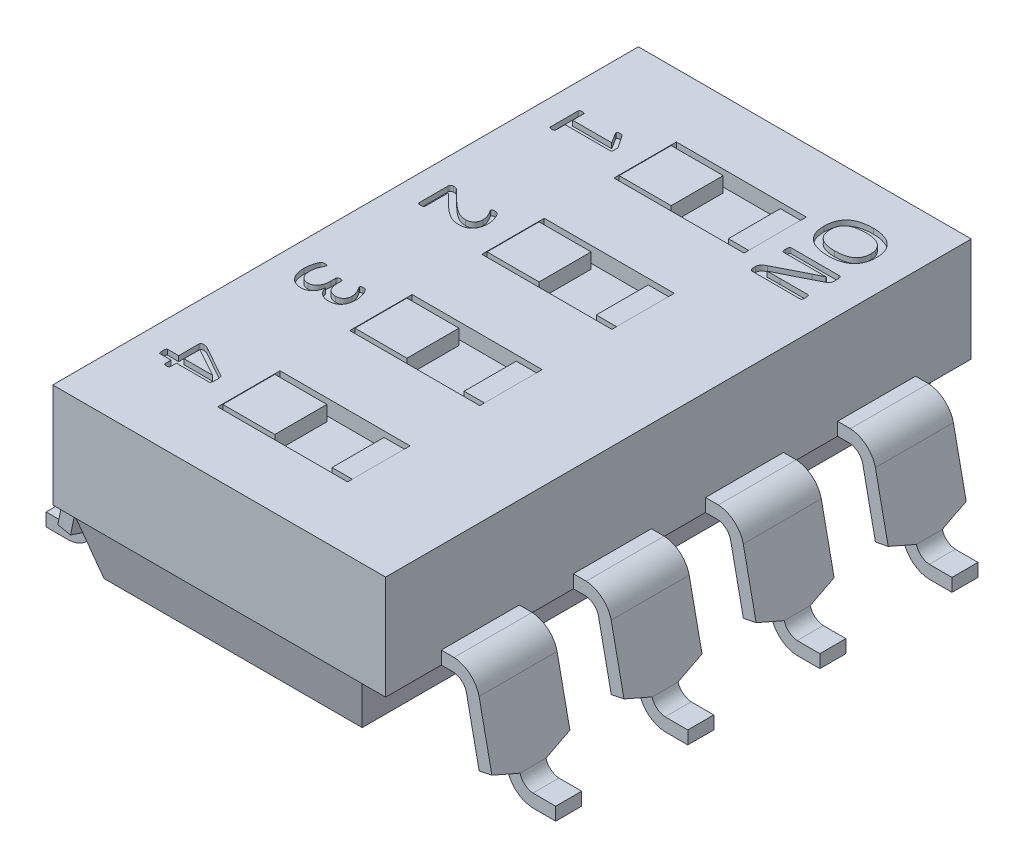
SolidWorks part; units mm, degrees
ref_plane "Спереди" through (0, 0, 0) normal (0, 0, 1) x (1, 0, 0)
ref_plane "Сверху" through (0, 0, 0) normal (0, 1, 0) x (1, 0, 0)
ref_plane "Справа" through (0, 0, 0) normal (1, 0, 0) x (0, 0, -1)
sketch "Sketch1" plane through (0, 0, 0) normal (0, 0, 1) x (1, 0, 0)
  line L0 (66.6635, 160.3935) -> (333.3177, 160.3935) construction
  line L1 (0, 2) -> (6.4, 2)
  line L2 (6.4, 2) -> (6.4, 0)
  line L3 (6.4, 0) -> (0, 0)
  line L4 (0, 0) -> (0, 2)
  line L5 (2.3203, 4.3795) -> (2.0786, 4.3795) construction
  line L6 (1.7154, 4.0687) -> (1.4279, 2.6817) construction
  line L7 (0.6203, 2.3795) -> (1.0626, 2.3795) construction
  arc A0 (1.0626, 2.3795) -> (1.4279, 2.6817) centre (1.0319, 2.7885) ccw construction
  arc A1 (2.0786, 4.3795) -> (1.7154, 4.0687) centre (2.1092, 3.9762) ccw construction
  dimension "D1" = 6.4
  dimension "D2" = 2
  dimension "D3" = 1.7
  dimension "D4" = 2
extrude "Boss-Extrude1" add sketch "Sketch1" along normal blind 11.26
sketch "Sketch3" plane through (0, 0, 0) normal (0, -1, 0) x (1, 0, 0)
  line L0 (0, 11.26) -> (6.4, 0) construction
  line L1 (0, 11.26) -> (6.4, 11.26) construction
  line L2 (0.45, 0) -> (5.95, 0)
  line L3 (0.45, 0) -> (0.45, 11.26)
  line L4 (0.45, 11.26) -> (5.95, 11.26)
  line L5 (5.95, 0) -> (5.95, 11.26)
  line L6 (0.45, 0) -> (5.95, 11.26) construction
  line L7 (0.45, 11.26) -> (5.95, 0) construction
  point P4 (3.2, 5.63)
  dimension "D1" = 5.5
extrude "Boss-Extrude2" add sketch "Sketch3" along normal blind 1 draft 15
ref_plane "Plane1" through (0, 0, 10.19) normal (0, 0, 1) x (1, 0, 0)
sketch "Sketch4" plane through (0, 0, 10.19) normal (0, 0, 1) x (1, 0, 0)
  line L0 (0, 0.125) -> (-0.2418, 0.125) construction
  line L1 (-0.6049, -0.1858) -> (-0.8924, -1.5729) construction
  line L2 (-1.7, -1.875) -> (-1.2578, -1.875) construction
  line L3 (7.9025, -1.875) -> (-1.7, -1.875) construction
  line L4 (6.4, 2) -> (0, 2) construction
  line L5 (0, 2) -> (0, 0) construction
  line L7 (0, 0.25) -> (-0.2462, 0.25)
  line L8 (-0.727, -0.159) -> (-1.014, -1.5435)
  line L9 (-1.7, -1.75) -> (-1.2629, -1.75)
  line L10 (0, 0) -> (-0.2366, 0)
  line L11 (-0.4829, -0.213) -> (-0.7707, -1.6016)
  line L12 (-1.7, -2) -> (-1.2534, -2)
  line L13 (-1.7, -1.75) -> (-1.7, -2)
  line L14 (0, 0) -> (0, 0.25)
  arc A0 (-1.2578, -1.875) -> (-0.8924, -1.5729) centre (-1.2884, -1.466) ccw construction
  arc A1 (-0.2418, 0.125) -> (-0.6049, -0.1858) centre (-0.2112, -0.2783) ccw construction
  arc A2 (-0.2462, 0.25) -> (-0.727, -0.159) centre (-0.2112, -0.2783) ccw
  arc A3 (-1.2629, -1.75) -> (-1.014, -1.5435) centre (-1.2884, -1.466) ccw
  arc A4 (-0.2366, 0) -> (-0.4829, -0.213) centre (-0.2112, -0.2783) ccw
  arc A5 (-1.2534, -2) -> (-0.7707, -1.6016) centre (-1.2884, -1.466) ccw
  dimension "D1" = 1.7
  dimension "D2" = 2
  dimension "D3" = 3.875
  dimension "D4" = 0.125
  dimension "D5" = 0.125
extrude "Boss-Extrude3" add sketch "Sketch4" against normal blind 1.5
sketch "Sketch5" plane through (-0.6655, 0.1379, 0) normal (-0.9792, 0.203, 0) x (0, 0, 1)
  line L0 (9.44, -0.3032) -> (9.44, -1.7172) construction
  line L1 (8.69, -0.3032) -> (10.19, -0.3032) construction
  line L2 (8.69, -1.7172) -> (10.19, -1.7172) construction
  line L3 (9.44, -1.7172) -> (9.69, -1.7172) construction
  line L4 (9.69, -1.7172) -> (10.19, -1.5172)
  line L5 (9.69, -1.7172) -> (10.19, -1.7172)
  line L6 (10.19, -1.7172) -> (10.19, -1.5172)
  line L7 (10.19, -0.3032) -> (10.19, -1.7172) construction
  line L8 (8.69, -1.7172) -> (8.69, -1.5172)
  line L9 (9.19, -1.7172) -> (8.69, -1.7172)
  line L10 (9.19, -1.7172) -> (8.69, -1.5172)
  dimension "D1" = 0.25
  dimension "D2" = 0.2
extrude "Cut-Extrude1" cut sketch "Sketch5" against normal through all
sketch "Sketch6" plane through (-0.3486, -1.6815, 0) normal (0.203, 0.9792, 0) x (0.9792, -0.203, 0)
  line L1 (-0.4296, -9.69) -> (-1.5055, -9.69)
  line L2 (-0.4296, -9.69) -> (-0.4296, -10.2349)
  line L3 (-0.4296, -10.2349) -> (-1.5055, -10.2349)
  line L4 (-1.5055, -9.69) -> (-1.5055, -10.2349)
  line L5 (-0.4296, -9.19) -> (-1.5055, -9.19)
  line L6 (-0.4296, -9.19) -> (-0.4296, -8.6481)
  line L7 (-0.4296, -8.6481) -> (-1.5055, -8.6481)
  line L8 (-1.5055, -9.19) -> (-1.5055, -8.6481)
extrude "Cut-Extrude2" cut sketch "Sketch6" against normal through all
pattern_linear "LPattern1" count 4 spacing 2.54 along (0, 0, -1) of "Boss-Extrude3", "Cut-Extrude1", "Cut-Extrude2"
ref_plane "Plane2" through (3.2, 0, 0) normal (-1, 0, 0) x (0, 0, 1)
mirror "Mirror1" about plane through (3.2, 0, 0) normal (-1, 0, 0) of "LPattern1", "Cut-Extrude2", "Cut-Extrude1", "Boss-Extrude3"
sketch "Sketch7" plane through (0, 2, 0) normal (0, 1, 0) x (1, 0, 0)
  line L0 (-1.7, -1.82) -> (8.1, -1.82) construction
  line L1 (-1.7, -1.57) -> (-1.7, -2.07) construction
  line L2 (8.1, -1.57) -> (8.1, -2.07) construction
  line L3 (1.95, -4.96) -> (4.45, -4.96)
  line L4 (1.95, -2.42) -> (4.45, -2.42)
  line L5 (1.95, -2.42) -> (1.95, -1.22)
  line L6 (1.95, -1.22) -> (4.45, -1.22)
  line L7 (4.45, -2.42) -> (4.45, -1.22)
  line L8 (1.95, -2.42) -> (4.45, -1.22) construction
  line L9 (1.95, -1.22) -> (4.45, -2.42) construction
  line L10 (1.95, -4.96) -> (1.95, -3.76)
  line L11 (1.95, -3.76) -> (4.45, -3.76)
  line L12 (4.45, -4.96) -> (4.45, -3.76)
  line L13 (1.95, -4.96) -> (4.45, -3.76) construction
  line L14 (1.95, -3.76) -> (4.45, -4.96) construction
  line L15 (1.95, -7.5) -> (4.45, -7.5)
  line L16 (1.95, -7.5) -> (1.95, -6.3)
  line L17 (1.95, -6.3) -> (4.45, -6.3)
  line L18 (4.45, -7.5) -> (4.45, -6.3)
  line L19 (1.95, -7.5) -> (4.45, -6.3) construction
  line L20 (1.95, -6.3) -> (4.45, -7.5) construction
  line L21 (1.95, -10.04) -> (4.45, -10.04)
  line L22 (1.95, -10.04) -> (1.95, -8.84)
  line L23 (1.95, -8.84) -> (4.45, -8.84)
  line L24 (4.45, -10.04) -> (4.45, -8.84)
  line L25 (1.95, -10.04) -> (4.45, -8.84) construction
  line L26 (1.95, -8.84) -> (4.45, -10.04) construction
  point P6 (3.2, -1.82)
  point P13 (3.2, -4.36)
  point P18 (3.2, -6.9)
  point P23 (3.2, -9.44)
  dimension "D1" = 1.2
  dimension "D2" = 2.5
  dimension "D3" = 4
extrude "Cut-Extrude3" cut sketch "Sketch7" against normal blind 0.5
sketch "Sketch8" plane through (0, 1.5, 0) normal (0, 1, 0) x (1, 0, 0)
  line L1 (1.95, -1.22) -> (4.45, -1.22)
  line L2 (1.95, -1.22) -> (1.95, -2.42)
  line L3 (1.95, -2.42) -> (4.45, -2.42)
  line L4 (4.45, -1.22) -> (4.45, -2.42)
extrude "Boss-Extrude4" add sketch "Sketch8" along normal blind 0.2
sketch "Sketch9" plane through (0, 1.7, 0) normal (0, 1, 0) x (1, 0, 0)
  line L1 (1.95, -1.22) -> (1.95, -2.42) construction
  line L2 (1.95, -1.32) -> (2.95, -1.32)
  line L3 (1.95, -1.32) -> (1.95, -2.32)
  line L4 (1.95, -2.32) -> (2.95, -2.32)
  line L5 (2.95, -1.32) -> (2.95, -2.32)
  line L6 (2.95, -1.82) -> (4.45, -1.82) construction
  line L7 (4.45, -1.32) -> (4.05, -1.32)
  line L8 (4.45, -1.32) -> (4.45, -2.32)
  line L9 (4.45, -2.32) -> (4.05, -2.32)
  line L10 (4.05, -1.32) -> (4.05, -2.32)
  line L11 (4.45, -2.42) -> (4.45, -1.22) construction
  dimension "D1" = 1
  dimension "D2" = 1
  dimension "D3" = 1.1
extrude "Boss-Extrude5" add sketch "Sketch9" along normal blind 0.29
pattern_linear "LPattern2" count 4 spacing 2.54 along (0, 0, 1) of "Boss-Extrude4", "Boss-Extrude5"
sketch "Sketch10" plane through (0, 2, 0) normal (0, 1, 0) x (1, 0, 0)
  line L0 (4.7846, -0.6876) -> (4.7846, -3.1383) construction
  line L1 (0.4883, -1.4718) -> (0.4883, -3.0178) construction
  line L2 (0.4883, -4.0118) -> (0.4883, -5.5578) construction
  line L3 (0.4883, -6.5518) -> (0.4883, -8.0978) construction
  line L4 (0.4883, -9.0918) -> (0.4883, -10.6378) construction
  text T0 "ON" font "Calibri" height 1
  text T2 "1" font "Calibri" height 1
  text T3 "2" font "Calibri" height 1
  text T4 "3" font "Calibri" height 1
  text T5 "4" font "Calibri" height 1
  dimension "D1" = 4
extrude "Вырез-Вытянуть1" cut sketch "Sketch10" against normal blind 0.1
